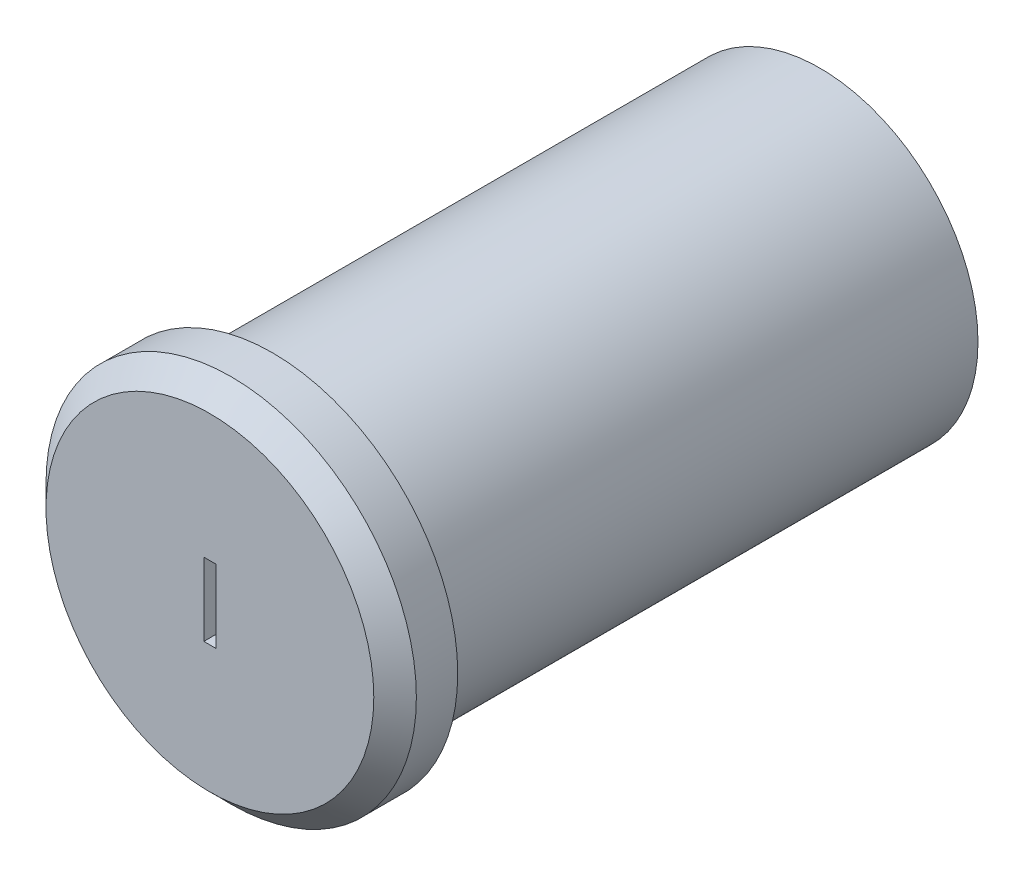
SolidWorks part; units mm, degrees
ref_plane "Front" through (0, 0, 0) normal (0, 0, 1) x (1, 0, 0)
ref_plane "Top" through (0, 0, 0) normal (0, 1, 0) x (1, 0, 0)
ref_plane "Right" through (0, 0, 0) normal (1, 0, 0) x (0, 0, -1)
sketch "Sketch1" plane through (0, 0, 0) normal (0, 0, 1) x (1, 0, 0)
  circle A0 centre (0, 0) radius 13
  dimension "D1" = 26
extrude "Boss-Extrude1" add sketch "Sketch1" against normal blind 45
sketch "Sketch2" plane through (0, 0, 0) normal (0, 0, 1) x (1, 0, 0)
  circle A0 centre (0, 0) radius 15.225
  dimension "D1" = 30.45
extrude "Boss-Extrude2" add sketch "Sketch2" along normal blind 3.4
sketch "Sketch3" plane through (0, 0, 3.4) normal (0, 0, 1) x (1, 0, 0)
  circle A1 centre (0, 0) radius 15.225
  circle A2 centre (0, 0) radius 15.225
  dimension "D1" = 0
extrude "Boss-Extrude3" add sketch "Sketch3" along normal blind 1.75 draft 45
sketch "Sketch4" plane through (0, 0, 5.15) normal (0, 0, 1) x (1, 0, 0)
  line L1 (-0.5, -3) -> (0.5, -3)
  line L2 (-0.5, -3) -> (-0.5, 3)
  line L3 (-0.5, 3) -> (0.5, 3)
  line L4 (0.5, -3) -> (0.5, 3)
  line L5 (-0.5, -3) -> (0.5, 3) construction
  line L6 (-0.5, 3) -> (0.5, -3) construction
  point P0 (0, 0)
  dimension "D1" = 1
  dimension "D2" = 6
extrude "Cut-Extrude1" cut sketch "Sketch4" against normal blind 1
sketch "Panel Cut Guide" plane through (0, 0, 0) normal (0, 0, 1) x (1, 0, 0)
  line L0 (0, 0) -> (0, -14.9746) construction
  line L3 (-2.75, -13.1148) -> (-2.75, -14.9746)
  line L4 (-2.75, -14.9746) -> (2.75, -14.9746)
  line L5 (2.75, -14.9746) -> (2.75, -13.1148)
  arc A3 (2.75, -13.1148) -> (-2.75, -13.1148) centre (0, 0) ccw
  circle A4 centre (0, 0) radius 15.225 construction
  dimension "D1" = 26.8
  dimension "D2" = 5.5
ref_plane "Panel Thickness Depth" through (0, 0, -2.2) normal (0, 0, 1) x (1, 0, 0)
